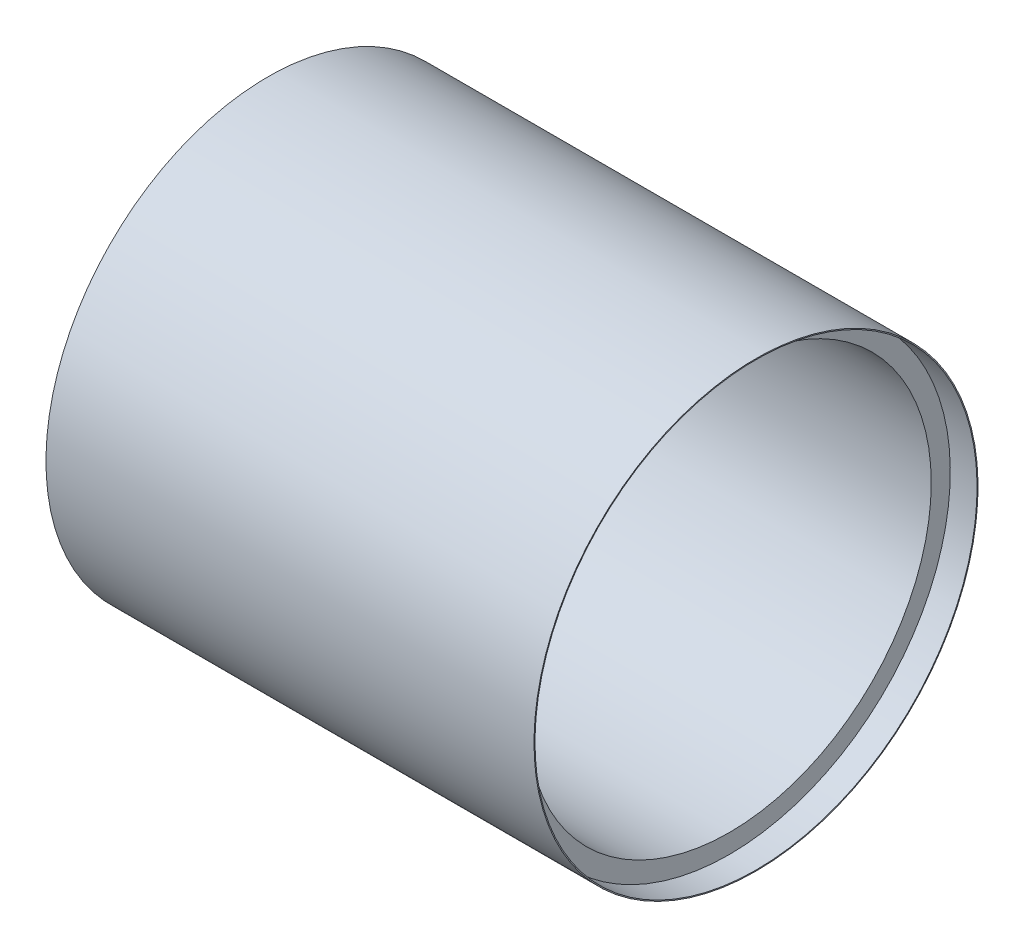
SolidWorks part; units mm, degrees
material "Carbon sandwich"
ref_plane "Front" through (0, 0, 0) normal (0, 0, 1) x (1, 0, 0)
ref_plane "Top" through (0, 0, 0) normal (0, 1, 0) x (1, 0, 0)
ref_plane "Right" through (0, 0, 0) normal (1, 0, 0) x (0, 0, -1)
sketch "Sketch1" plane through (0, 0, 0) normal (0, 0, 1) x (1, 0, 0)
  line L0 (39.1463, 83.9724) -> (49.3063, 83.9724)
  line L1 (49.3063, 83.9724) -> (49.3063, 76.7334)
  line L2 (49.3063, 76.7334) -> (214.4063, 76.7334)
  line L3 (214.4063, 76.7334) -> (214.4063, 83.9724)
  line L4 (214.4063, 83.9724) -> (224.5663, 83.9724)
  line L5 (224.5663, 83.9724) -> (224.5663, 84.3534)
  line L6 (224.5663, 84.3534) -> (39.1463, 84.3534)
  line L7 (39.1463, 84.3534) -> (39.1463, 83.9724)
  line L8 (0, 0) -> (134.0356, 0) construction
  dimension "D1" = 76.7334
  dimension "D2" = 0.381
  dimension "D3" = 10.16
  dimension "D4" = 10.16
  dimension "D5" = 165.1
  dimension "D6" = 84.3534
  dimension "D7" = 0.381
revolve "Revolve1" add sketch "Sketch1" angle 360 about L8
